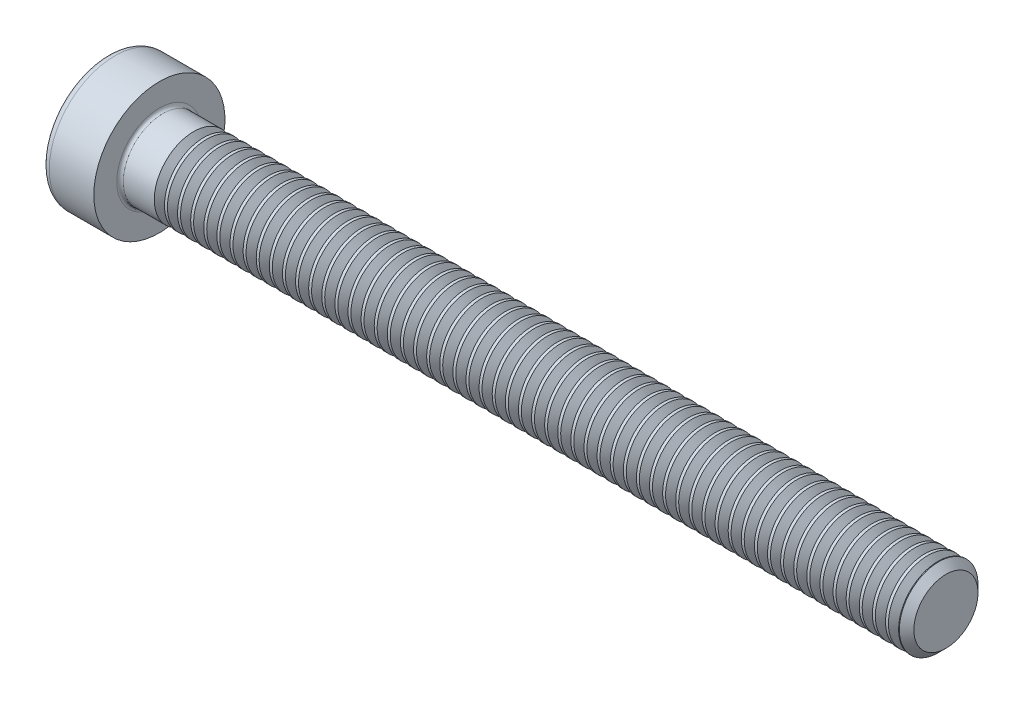
SolidWorks part; units mm, degrees
ref_plane "Plane1" through (0, 0, 0) normal (0, 0, 1) x (1, 0, 0)
ref_plane "Plane2" through (0, 0, 0) normal (0, 1, 0) x (1, 0, 0)
ref_plane "Plane3" through (0, 0, 0) normal (1, 0, 0) x (0, 0, -1)
sketch "BodySke" plane through (0, 0, 0) normal (0, 0, 1) x (1, 0, 0)
  line L0 (0, 0) -> (0, 5)
  line L1 (0, 5) -> (4, 5)
  line L2 (4, 5) -> (4, 3)
  line L3 (4, 3) -> (63.4455, 3)
  line L4 (64, 2.4455) -> (64, 0)
  line L5 (64, 0) -> (0, 0)
  line L6 (-31.75, 0) -> (127, 0) construction
  line L8 (64, 2.4455) -> (63.4455, 3)
  line L10 (64, -2.4455) -> (63.4455, -3) construction
  line L11 (5, 4.525) -> (5, -1.825) construction
  line L12 (4, 4.525) -> (4, -1.825) construction
  line L13 (4, 4.525) -> (4, -1.825) construction
  dimension "Diameter" = 6
  dimension "Head_ht" = 4
  dimension "Length" = 60
  dimension "Body_ch_ang" = 45
  dimension "Head_dia" = 10
  dimension "Minor_dia" = 4.891
  dimension "Advance" = 1
  dimension "Thread_nom" = 60
  dimension "Thread_length" = 60
revolve "Base-Revolve" add sketch "BodySke"
cosmetic thread "ThreadCosmetic" [suppressed]
fillet "Fillet1" radius 0.25 1 edges at (4, 0, 3)
fillet "Fillet2" radius 0.6 1 edges at (0, 0, 5)
sketch "HexSke" plane through (0, 0, 0) normal (-1, 0, 0) x (0, 0.5, 0.866)
  line L0 (1.4434, 2.5) -> (-1.4434, 2.5)
  line L1 (-1.4434, 2.5) -> (-2.8868, 0)
  line L2 (1.4434, 2.5) -> (2.8868, 0)
  line L3 (1.4434, -2.5) -> (2.8868, 0)
  line L4 (1.4434, -2.5) -> (-1.4434, -2.5)
  line L5 (-1.4434, -2.5) -> (-2.8868, 0)
  dimension "D1" = 2.5
  dimension "D2" = 2.5
  dimension "Hex_size" = 5
extrude "Hex" cut sketch "HexSke" against normal blind 2.5
sketch "PilotSke" plane through (0, 0, 0) normal (0, 0, 1) x (1, 0, 0)
  line L0 (0, 2.5) -> (2.5, 2.5)
  line L1 (2.5, 2.5) -> (3.0774, 1.5)
  line L2 (-31.75, 0) -> (127, 0) construction
  line L3 (5.866, 0) -> (0, 0)
  line L4 (0, 0) -> (0, 2.5)
  line L5 (3.0774, 1.5) -> (5, 1.5)
  line L6 (0, 0) -> (47.625, 0) construction
  line L7 (5, 1.5) -> (5.866, 0)
  dimension "D1" = 2.5
  dimension "D2" = 60
  dimension "Depth" = 2.5
  dimension "Pilot_dia" = 3
  dimension "Pilot_Depth" = 5
revolve "Hex-PreBroach" cut sketch "PilotSke" angle 360 about L6
sketch "ThdSchSke" plane through (0, 0, 0) normal (0, 0, 1) x (1, 0, 0)
  line L0 (7, -2.4455) -> (6.6117, -3)
  line L1 (7, -2.4455) -> (7.3883, -3)
  line L2 (7.3883, -3) -> (7.3883, -3.75)
  line L3 (-3.175, 0) -> (5.1513, 0) construction
  line L4 (0, 4.4) -> (0, -4.4) construction
  line L5 (7.3883, -3.75) -> (6.6117, -3.75)
  line L6 (6.6117, -3.75) -> (6.6117, -3)
  dimension "Thread_minor" = 4.891
  dimension "Diameter" = 6
  dimension "Start" = 7
  dimension "SideAngle" = 55
  dimension "VeeAngle" = 70
  dimension "Overcut" = 7.5
revolve "ThreadSchematic" cut sketch "ThdSchSke" angle 360 about L3
pattern_linear "ThdSchPat" count 57 spacing 1 along (1, 0, 0) of "ThreadSchematic"
equation "\"D2@HexSke\" = \"Hex_size@HexSke\" / 2"
equation "\"D1@HexSke\" = \"Hex_size@HexSke\" / 2"
equation "\"D1@PilotSke\" = \"Hex_size@HexSke\" / 2"
equation "\"Thread_minor@ThreadCosmetic\"  =  \"Minor_dia@BodySke\""
equation "\"Depth@PilotSke\" =  \"Key_eng@Hex\""
equation "\"Thread_length@ThreadCosmetic\" = ((sgn( (\"Length@BodySke\" - \"Advance@BodySke\" * 3.0) - \"Thread_nom@BodySke\" )-1)*( (\"Length@BodySke\" - \"Advance@BodySke\" * 3.0) - \"Thread_nom@BodySke\" ))/-2+ \"Thread_nom@BodySke\""
equation "\"Thread_minor@ThdSchSke\" = \"Minor_dia@BodySke\""
equation "\"Diameter@ThdSchSke\" = \"Diameter@BodySke\""
equation "\"Overcut@ThdSchSke\" = \"Diameter@BodySke\" * 1.25"
equation "\"Start@ThdSchSke\" = \"Head_ht@BodySke\" + \"Length@BodySke\" - \"Thread_length@ThreadCosmetic\"  '---Non-countersunk---"
equation "\"Num_threads@ThdSchPat\" = int( \"Thread_length@ThreadCosmetic\" / \"Advance@BodySke\" + 0.999 )  + 1"
equation "\"Advance@ThdSchPat\" = \"Thread_length@ThreadCosmetic\" /  (\"Num_threads@ThdSchPat\" - 1) 'relax it"
equation "\"Num_threads@ThdSchPat\" = \"Num_threads@ThdSchPat\" - sgn( \"Num_threads@ThdSchPat\" - 1) '---chamfered tips only---"
